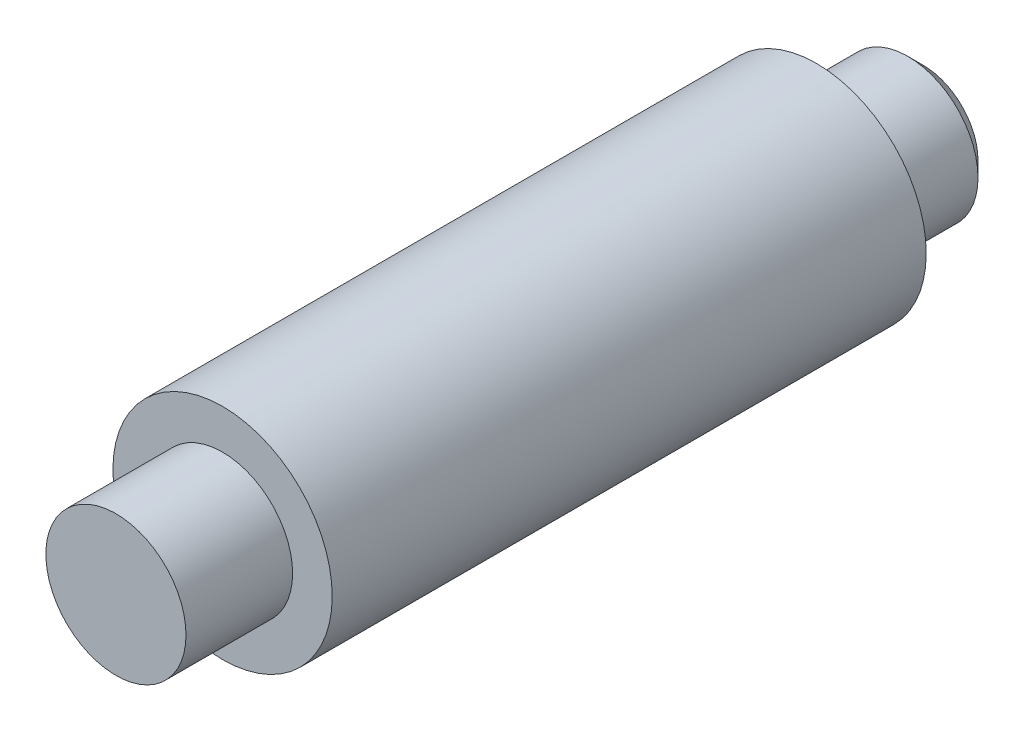
SolidWorks part; units mm, degrees
ref_plane "Front Plane" through (0, 0, 0) normal (0, 0, 1) x (1, 0, 0)
ref_plane "Top Plane" through (0, 0, 0) normal (0, 1, 0) x (1, 0, 0)
ref_plane "Right Plane" through (0, 0, 0) normal (1, 0, 0) x (0, 0, -1)
sketch "Sketch2" plane through (0, 0, 0) normal (0, 0, 1) x (1, 0, 0)
  circle A0 centre (0, 0) radius 1.25
  dimension "D1" = 2.5
sketch "Sketch3" plane through (0, 0, 0) normal (0, 0, 1) x (1, 0, 0)
  line L5 (-3.6, 3.6) -> (3.6, 3.6) construction
  line L6 (-3.6, 3.6) -> (-3.6, -3.6) construction
  line L7 (-3.6, -3.6) -> (3.6, -3.6) construction
  line L8 (3.6, 3.6) -> (3.6, -3.6) construction
  circle A0 centre (0, 0) radius 3.6
  point P4 (0, 3.6)
  point P6 (-3.6, 0)
  dimension "D1" = 7.2
extrude "Boss-Extrude1" add sketch "Sketch3" along normal blind 19.5
sketch "Sketch4" plane through (0, 0, 0) normal (0, 0, 1) x (1, 0, 0)
  circle A0 centre (0, 0) radius 2.3
  dimension "D1" = 4.6
extrude "Boss-Extrude2" add sketch "Sketch4" against normal blind 3.5
sketch "Sketch5" plane through (0, 0, 19.5) normal (0, 0, 1) x (1, 0, 0)
  circle A0 centre (0, 0) radius 2.3
  dimension "D1" = 4.6
extrude "Boss-Extrude3" add sketch "Sketch5" along normal blind 3.5
chamfer "Chamfer1" distance 0.5 angle 45 1 edges at (2.3, 0, -3.5)
equation "\"length\"=19.5"
equation "\"D1@Boss-Extrude1\"=\"length\""
equation "\"holer\"=4.6"
equation "\"D1@Sketch5\"=\"holer\""
equation "\"D1@Sketch4\"=\"holer\""
equation "\"pin\"=3.5"
equation "\"D1@Boss-Extrude2\"=\"pin\""
equation "\"D1@Boss-Extrude3\"=\"pin\""
